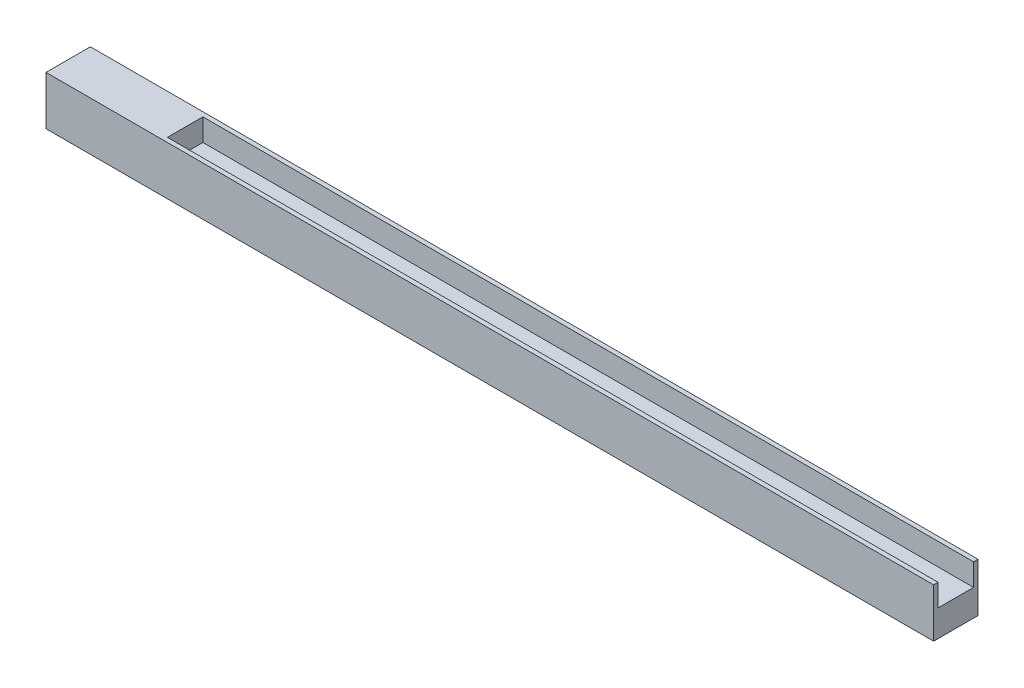
SolidWorks part; units mm, degrees
ref_plane "Front Plane" through (0, 0, 0) normal (0, 0, 1) x (1, 0, 0)
ref_plane "Top Plane" through (0, 0, 0) normal (0, 1, 0) x (1, 0, 0)
ref_plane "Right Plane" through (0, 0, 0) normal (1, 0, 0) x (0, 0, -1)
sketch "Sketch1" plane through (0, 0, 0) normal (0, 0, 1) x (1, 0, 0)
  line L1 (0, 0) -> (254, 0)
  line L2 (0, 0) -> (0, -13.97)
  line L3 (0, -13.97) -> (254, -13.97)
  line L4 (254, 0) -> (254, -13.97)
  line L5 (0, 0) -> (254, -13.97) construction
  line L6 (0, -13.97) -> (254, 0) construction
  point P4 (127, -6.985)
  dimension "D1" = 254
  dimension "D2" = 13.97
extrude "Boss-Extrude1" add sketch "Sketch1" along normal blind 12.7
sketch "Sketch2" plane through (0, 0, 0) normal (0, 1, 0) x (1, 0, 0)
  line L0 (254, -12.7) -> (254, 0) construction
  line L1 (254, -1.27) -> (33.4639, -1.27)
  line L2 (254, -1.27) -> (254, -11.43)
  line L3 (254, -11.43) -> (33.4639, -11.43)
  line L4 (33.4639, -1.27) -> (33.4639, -11.43)
  line L5 (254, -1.27) -> (33.4639, -11.43) construction
  line L6 (254, -11.43) -> (33.4639, -1.27) construction
  line L7 (254, 0) -> (0, 0) construction
  line L8 (254, -12.7) -> (0, -12.7) construction
  point P4 (143.732, -6.35)
  dimension "D1" = 1.27
  dimension "D2" = 1.27
extrude "Cut-Extrude2" cut sketch "Sketch2" against normal blind 6.35
